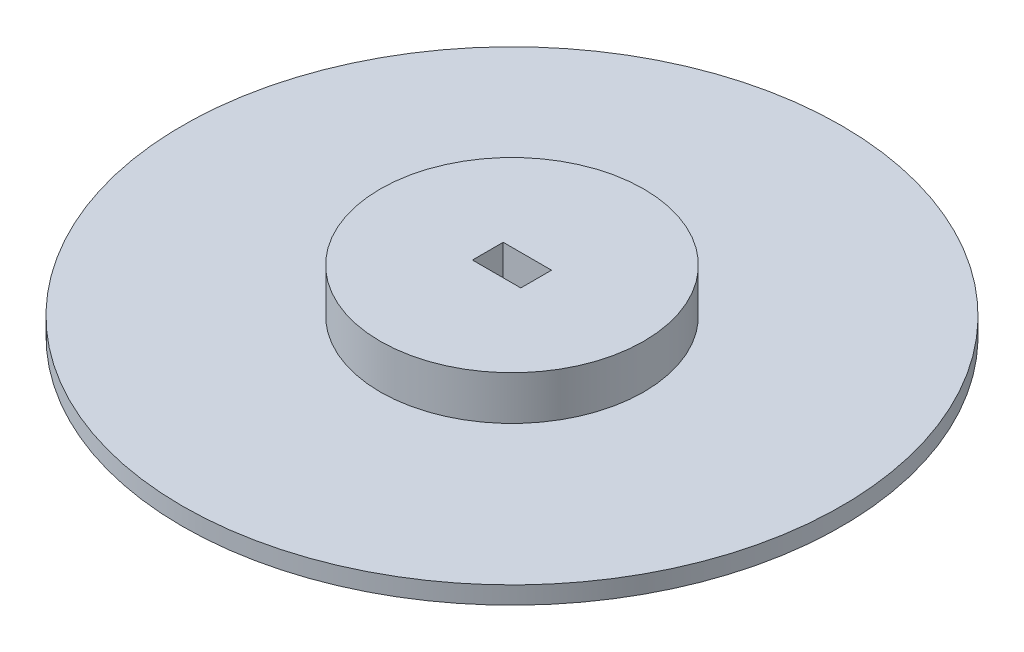
SolidWorks part; units mm, degrees
ref_plane "前视基准面" through (0, 0, 0) normal (0, 0, 1) x (1, 0, 0)
ref_plane "上视基准面" through (0, 0, 0) normal (0, 1, 0) x (1, 0, 0)
ref_plane "右视基准面" through (0, 0, 0) normal (1, 0, 0) x (0, 0, -1)
sketch "草图1" plane through (0, 0, 0) normal (0, 1, 0) x (1, 0, 0)
  circle A0 centre (0, 0) radius 15
extrude "凸台-拉伸1" add sketch "草图1" along normal blind 7
sketch "草图2" plane through (0, 7, 0) normal (0, 1, 0) x (1, 0, 0)
  line L4 (-2.75, -1.75) -> (-2.75, 1.75)
  line L5 (-2.75, -1.75) -> (2.75, -1.75)
  line L6 (-2.75, 1.75) -> (2.75, 1.75)
  line L7 (2.75, -1.75) -> (2.75, 1.75)
  line L8 (-2.75, -1.75) -> (2.75, 1.75) construction
  line L9 (-2.75, 1.75) -> (2.75, -1.75) construction
  point P1 (0, 0)
extrude "切除-拉伸1" cut sketch "草图2" against normal through all
sketch "草图3" plane through (0, 0, 0) normal (0, -1, 0) x (1, 0, 0)
  circle A0 centre (0, 0) radius 37.5
  circle A1 centre (0, 0) radius 10.3404
extrude "凸台-拉伸2" add sketch "草图3" against normal blind 2
